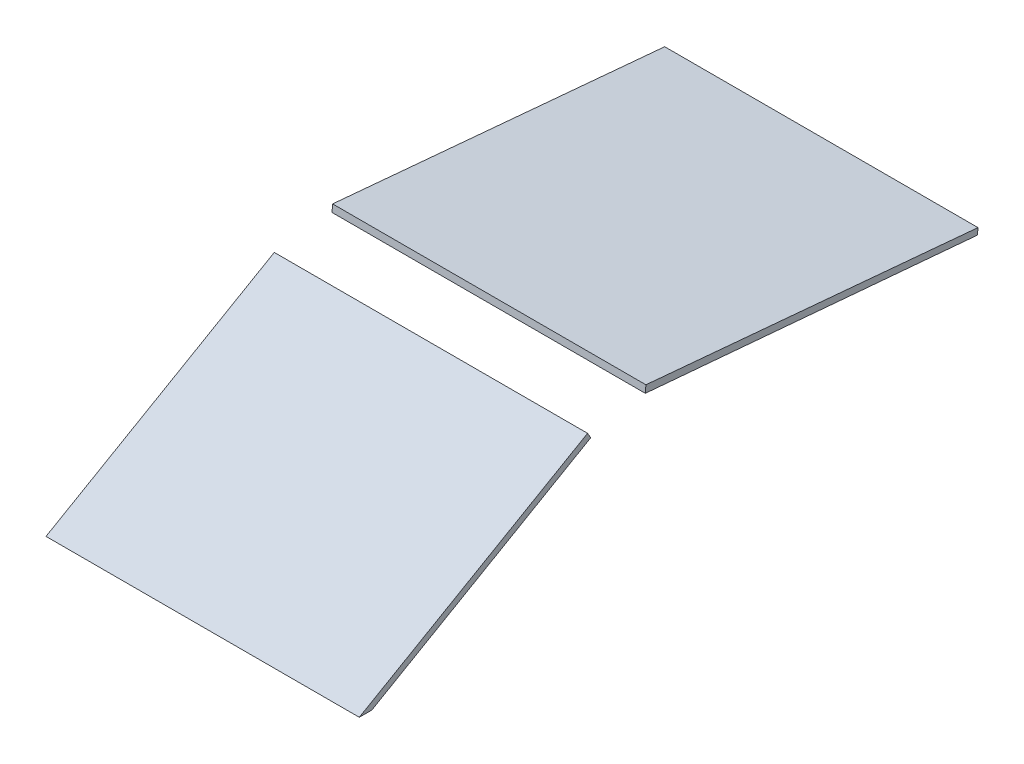
SolidWorks part; units mm, degrees
ref_plane "Front Plane" through (0, 0, 0) normal (0, 0, 1) x (1, 0, 0)
ref_plane "Top Plane" through (0, 0, 0) normal (0, 1, 0) x (1, 0, 0)
ref_plane "Right Plane" through (0, 0, 0) normal (1, 0, 0) x (0, 0, -1)
sketch "Sketch1" plane through (0, 0, 0) normal (1, 0, 0) x (0, 0, -1)
  line L0 (0, 0) -> (80186.3007, 0) construction
  line L1 (0, 0) -> (116.2899, 67.14)
  line L2 (116.2899, 67.14) -> (289.9665, 51.9453)
  line L3 (-6, 0) -> (0, 0)
  line L4 (116.2899, 67.14) -> (116.2899, 70.6041) construction
  line L5 (-6, 0) -> (116.2899, 70.6041)
  line L6 (289.9665, 51.9453) -> (290.2279, 54.9339)
  line L7 (290.2279, 54.9339) -> (116.2899, 70.6041)
  dimension "D1" = 134.28
  dimension "D2" = 30
  dimension "D3" = 145
  dimension "D4" = 174.34
  dimension "D5" = 3
  dimension "D6" = 3
extrude "Boss-Extrude1" add sketch "Sketch1" along normal blind 150
sketch "Sketch4" plane through (150, 0, 0) normal (1, 0, 0) x (0, 0, -1)
  line L0 (103.2995, 63.1041) -> (104.7995, 60.506)
  line L1 (116.2899, 70.6041) -> (-6, 0) construction
  line L2 (0, 0) -> (116.2899, 67.14) construction
  line L3 (103.2995, 63.1041) -> (116.2899, 70.6041)
  line L4 (116.2899, 70.6041) -> (131.2294, 69.2582)
  line L5 (290.2279, 54.9339) -> (116.2899, 70.6041) construction
  line L6 (131.2294, 69.2582) -> (130.932, 65.859)
  line L7 (116.2899, 67.14) -> (289.9665, 51.9453) construction
  line L8 (130.932, 65.859) -> (116.2899, 67.14)
  line L9 (116.2899, 67.14) -> (104.7995, 60.506)
  dimension "D1" = 15
  dimension "D2" = 15
extrude "Cut-Extrude1" cut sketch "Sketch4" against normal through all
